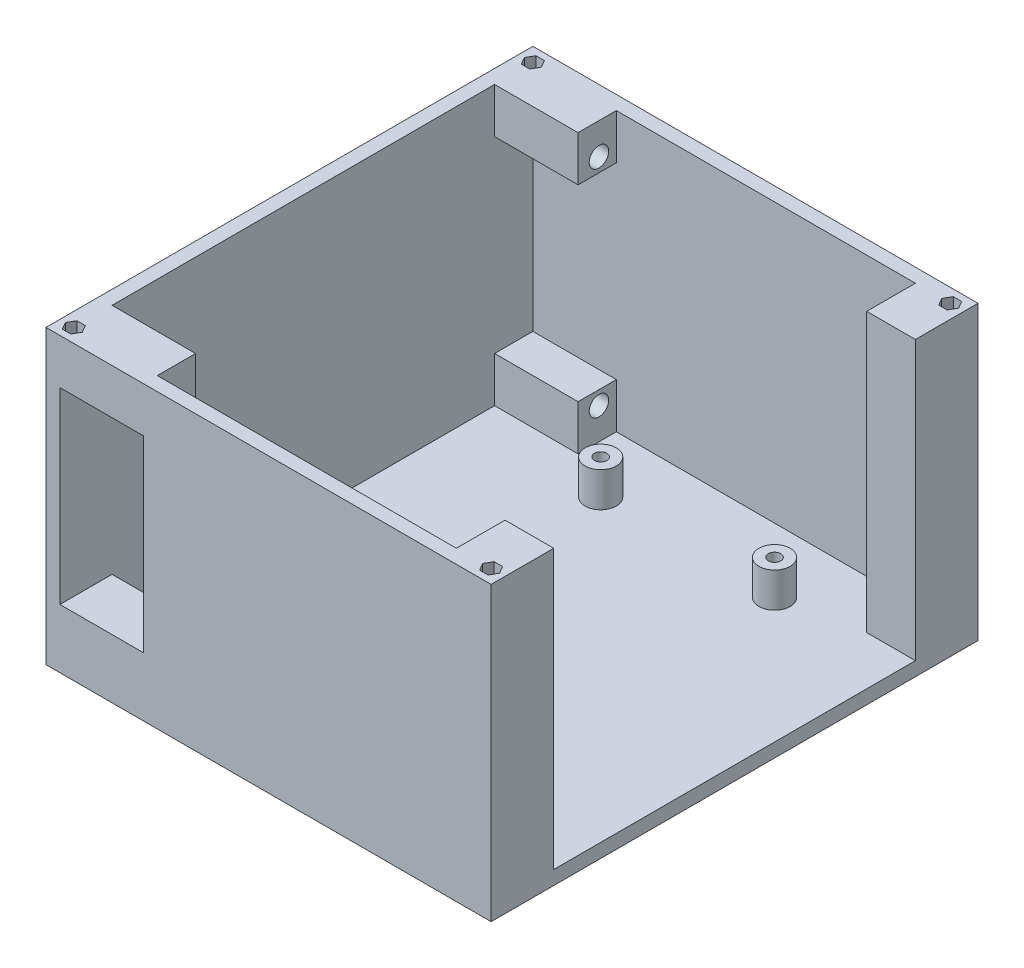
SolidWorks part; units mm, degrees
ref_plane "Front Plane" through (0, 0, 0) normal (0, 0, 1) x (1, 0, 0)
ref_plane "Top Plane" through (0, 0, 0) normal (0, 1, 0) x (1, 0, 0)
ref_plane "Right Plane" through (0, 0, 0) normal (1, 0, 0) x (0, 0, -1)
sketch "Sketch1" plane through (0, 0, 0) normal (0, 1, 0) x (1, 0, 0)
  line L1 (0, 0) -> (64, 0)
  line L2 (0, 0) -> (0, -70)
  line L3 (0, -70) -> (64, -70)
  line L4 (64, 0) -> (64, -70)
  dimension "D1" = 70
  dimension "D2" = 64
extrude "Boss-Extrude1" add sketch "Sketch1" along normal blind 2
sketch "Sketch2" plane through (0, 2, 0) normal (0, 1, 0) x (1, 0, 0)
  line L1 (0, 0) -> (64, 0)
  line L2 (0, 0) -> (0, -70)
  line L3 (0, -70) -> (64, -70)
  line L4 (64, 0) -> (64, -70)
  line L5 (14, -2) -> (57, -2)
  line L6 (2, -7.5) -> (2, -62.5)
  line L7 (14, -68) -> (57, -68)
  line L8 (62, -9) -> (62, -61)
  line L9 (2, -7.5) -> (14, -7.5)
  line L12 (14, -7.5) -> (14, -2)
  line L13 (2, -62.5) -> (14, -62.5)
  line L16 (14, -62.5) -> (14, -68)
  line L18 (57, -2) -> (57, -9)
  line L19 (57, -9) -> (62, -9)
  line L23 (62, -61) -> (57, -61)
  line L24 (57, -68) -> (57, -61)
  dimension "D1" = 2
  dimension "D2" = 2
  dimension "D3" = 2
  dimension "D4" = 2
  dimension "D5" = 12
  dimension "D6" = 55
  dimension "D7" = 52
  dimension "D8" = 5
extrude "Boss-Extrude2" add sketch "Sketch2" along normal blind 40
sketch "Sketch3" plane through (0, 2, 0) normal (0, 1, 0) x (1, 0, 0)
  line L0 (14, -68) -> (14, -58.75) construction
  line L1 (14, -58.75) -> (21, -58.75) construction
  line L2 (21, -11.25) -> (21, -2) construction
  line L3 (21, -58.75) -> (46, -58.75) construction
  line L4 (21, -58.75) -> (21, -11.25) construction
  line L5 (21, -11.25) -> (46, -11.25) construction
  line L6 (46, -58.75) -> (46, -11.25) construction
  line L7 (57, -2) -> (14, -2) construction
  circle A0 centre (21, -11.25) radius 0.9
  circle A1 centre (46, -11.25) radius 0.9
  circle A2 centre (21, -58.75) radius 2.25
  circle A3 centre (46, -58.75) radius 2.25
  circle A4 centre (21, -11.25) radius 2.25
  circle A5 centre (46, -11.25) radius 2.25
  circle A6 centre (21, -58.75) radius 0.9
  circle A7 centre (46, -58.75) radius 0.9
  dimension "D4" = 1.8
  dimension "D5" = 4.5
  dimension "D1" = 25
  dimension "D2" = 47.5
  dimension "D3" = 7
extrude "Boss-Extrude3" add sketch "Sketch3" along normal blind 5
sketch "Sketch4" plane through (64, 0, 0) normal (1, 0, 0) x (0, 0, -1)
  line L1 (-61, 42) -> (-9, 42)
  line L2 (-61, 42) -> (-61, 2)
  line L3 (-61, 2) -> (-9, 2)
  line L4 (-9, 42) -> (-9, 2)
  line L6 (-70, 0) -> (0, 0) construction
  line L7 (-70, 42) -> (0, 42) construction
  line L8 (-61, 2) -> (-70, 2) construction
  line L9 (-70, 42) -> (-70, 0) construction
  line L10 (-9, 2) -> (0, 2) construction
  line L11 (0, 42) -> (0, 0) construction
  dimension "D1" = 52
  dimension "D3" = 2
  dimension "D4" = 0
extrude "Cut-Extrude1" cut sketch "Sketch4" against normal up to surface (2 mm away) contours L2 L1 L4 L3 up to face at (62, 22, 35)
sketch "Sketch5" plane through (57, 0, 0) normal (-1, 0, 0) x (0, 0, 1)
  line L0 (2, 42) -> (7, 42) construction
  line L1 (0, 42) -> (70, 42) construction
  line L2 (7, 42) -> (63, 42) construction
  line L3 (63, 42) -> (68, 42) construction
  line L4 (68, 42) -> (70, 42) construction
  line L5 (0, 42) -> (0, 0) construction
  line L6 (7, 42) -> (7, 40) construction
  line L7 (7, 4) -> (7, 2) construction
  line L8 (7, 40) -> (63, 40) construction
  line L9 (7, 40) -> (7, 4) construction
  line L10 (7, 4) -> (63, 4) construction
  line L11 (63, 40) -> (63, 4) construction
  line L12 (7, 2) -> (7, 0) construction
  line L13 (0, 0) -> (70, 0) construction
  circle A0 centre (7, 40) radius 1
  circle A1 centre (7, 4) radius 1
  circle A2 centre (63, 4) radius 1
  circle A3 centre (63, 40) radius 1
  dimension "D6" = 2
  dimension "D1" = 2
  dimension "D2" = 2
  dimension "D3" = 56
  dimension "D4" = 2
  dimension "D5" = 36
extrude "Cut-Extrude4" cut sketch "Sketch5" against normal blind 4
sketch "Sketch6" plane through (0, 42, 0) normal (0, 1, 0) x (1, 0, 0)
  line L0 (64, -9) -> (64, 0) construction
  line L1 (2, -2) -> (62, -2) construction
  line L2 (2, -2) -> (2, -68) construction
  line L3 (2, -68) -> (62, -68) construction
  line L4 (62, -2) -> (62, -68) construction
  line L5 (64, 0) -> (0, 0) construction
  line L6 (0, 0) -> (0, -70) construction
  line L7 (0, -70) -> (64, -70) construction
  line L15 (3.2124, -2) -> (2.6062, -0.95)
  line L16 (2.6062, -0.95) -> (1.3938, -0.95)
  line L17 (1.3938, -0.95) -> (0.7876, -2)
  line L18 (0.7876, -2) -> (1.3938, -3.05)
  line L19 (1.3938, -3.05) -> (2.6062, -3.05)
  line L20 (2.6062, -3.05) -> (3.2124, -2)
  line L21 (3.2124, -68) -> (2.6062, -66.95)
  line L22 (2.6062, -66.95) -> (1.3938, -66.95)
  line L23 (1.3938, -66.95) -> (0.7876, -68)
  line L24 (0.7876, -68) -> (1.3938, -69.05)
  line L25 (1.3938, -69.05) -> (2.6062, -69.05)
  line L26 (2.6062, -69.05) -> (3.2124, -68)
  line L27 (60.7876, -68) -> (61.3938, -69.05)
  line L28 (61.3938, -69.05) -> (62.6062, -69.05)
  line L29 (62.6062, -69.05) -> (63.2124, -68)
  line L30 (63.2124, -68) -> (62.6062, -66.95)
  line L31 (62.6062, -66.95) -> (61.3938, -66.95)
  line L32 (61.3938, -66.95) -> (60.7876, -68)
  line L33 (60.7876, -2) -> (61.3938, -3.05)
  line L34 (61.3938, -3.05) -> (62.6062, -3.05)
  line L35 (62.6062, -3.05) -> (63.2124, -2)
  line L36 (63.2124, -2) -> (62.6062, -0.95)
  line L37 (62.6062, -0.95) -> (61.3938, -0.95)
  line L38 (61.3938, -0.95) -> (60.7876, -2)
  circle A0 centre (62, -2) radius 1.05 construction
  circle A1 centre (2, -2) radius 1.05 construction
  circle A2 centre (2, -68) radius 1.05 construction
  circle A3 centre (62, -68) radius 1.05 construction
  dimension "D5" = 2.1
  dimension "D1" = 2
  dimension "D2" = 2
  dimension "D3" = 2
  dimension "D4" = 2
extrude "Cut-Extrude5" cut sketch "Sketch6" against normal blind 2.3
sketch "Sketch7" plane through (14, 0, 0) normal (1, 0, 0) x (0, 0, -1)
  line L0 (-70, 37.5) -> (-65.5, 37.5) construction
  line L1 (-70, 42) -> (-70, 0) construction
  line L2 (-65.5, 37.5) -> (-4.5, 37.5) construction
  line L3 (-4.5, 37.5) -> (0, 37.5) construction
  line L4 (0, 42) -> (0, 0) construction
  line L5 (-65.5, 42) -> (-65.5, 37.5) construction
  line L6 (-70, 42) -> (-61, 42) construction
  line L7 (-65.5, 37.5) -> (-65.5, 6.5) construction
  line L8 (-65.5, 6.5) -> (-65.5, 2) construction
  line L9 (-65.5, 2) -> (-65.5, 0) construction
  line L10 (-70, 0) -> (0, 0) construction
  line L11 (-65.5, 6.5) -> (-4.5, 6.5) construction
  circle A0 centre (-65.5, 37.5) radius 1.4
  circle A1 centre (-4.5, 37.5) radius 1.4
  circle A2 centre (-65.5, 6.5) radius 1.4
  circle A3 centre (-4.5, 6.5) radius 1.4
  dimension "D4" = 2.8
  dimension "D1" = 61
  dimension "D2" = 2
  dimension "D3" = 31
extrude "Cut-Extrude6" cut sketch "Sketch7" against normal up to surface (12 mm away) up to face at (2, 22, 35)
sketch "Sketch8" plane through (0, 0, 70) normal (0, 0, 1) x (1, 0, 0)
  line L0 (14, 42) -> (14, 35.5) construction
  line L1 (0, 42) -> (64, 42) construction
  line L2 (14, 35.5) -> (14, 8.5) construction
  line L3 (14, 8.5) -> (14, 2) construction
  line L4 (14, 2) -> (14, 0) construction
  line L5 (0, 0) -> (64, 0) construction
  line L6 (0, 42) -> (0, 0) construction
  line L8 (14, 35.5) -> (2, 35.5)
  line L9 (14, 35.5) -> (14, 8.5)
  line L10 (14, 8.5) -> (2, 8.5)
  line L11 (2, 35.5) -> (2, 8.5)
  dimension "D1" = 2
  dimension "D2" = 14
  dimension "D3" = 12
  dimension "D4" = 27
extrude "Cut-Extrude7" cut sketch "Sketch8" against normal up to surface (68 mm away) up to face at (35.5, 22, 2)
